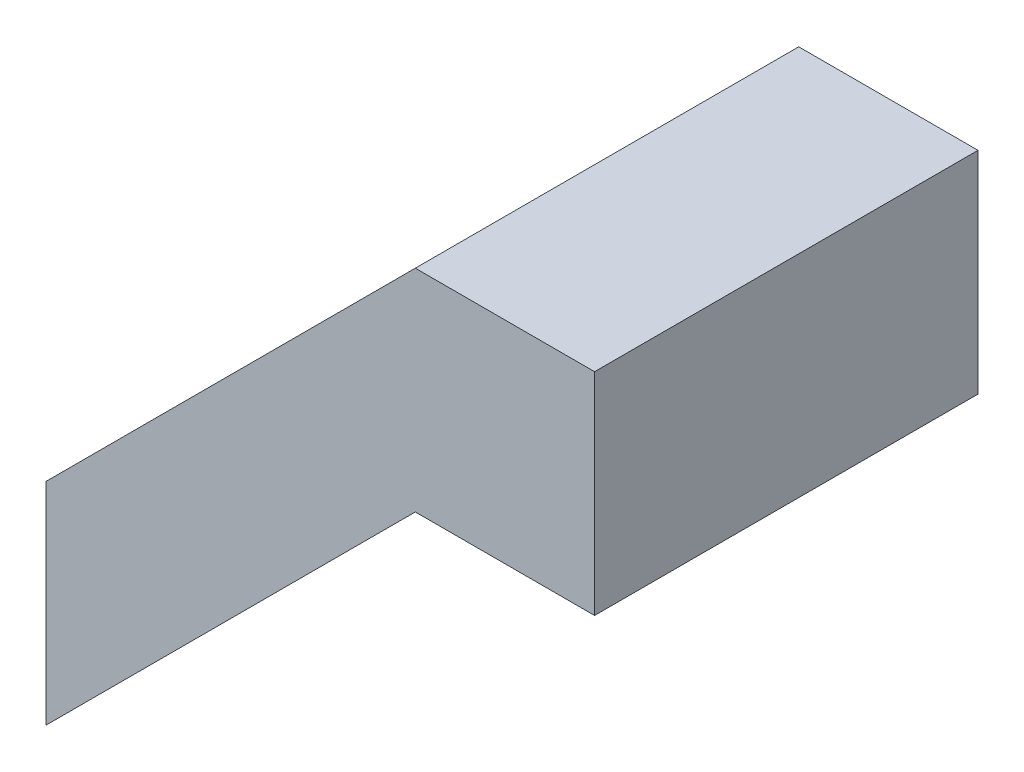
SolidWorks part; units mm, degrees
ref_plane "Alzado" through (0, 0, 0) normal (0, 0, 1) x (1, 0, 0)
ref_plane "Planta" through (0, 0, 0) normal (0, 1, 0) x (1, 0, 0)
ref_plane "Vista lateral" through (0, 0, 0) normal (1, 0, 0) x (0, 0, -1)
sketch "Croquis1" plane through (0, 0, 0) normal (0, 0, 1) x (1, 0, 0)
  line L0 (126.2451, -55.9999) -> (126.2451, -50.9999)
  line L1 (113.2545, -64.7452) -> (113.2545, -59.7452)
  line L2 (121.9998, -55.9999) -> (121.9998, -50.9999) construction
  line L3 (126.2451, -50.9999) -> (121.9998, -50.9999)
  line L4 (121.9998, -50.9999) -> (113.2545, -59.7452)
  line L5 (126.2451, -55.9999) -> (121.9998, -55.9999)
  line L7 (113.2545, -64.7452) -> (115.2545, -62.7452)
  line L8 (115.2545, -62.7452) -> (115.2545, -60.2452)
  line L15 (119.2545, -58.7452) -> (119.2545, -56.2452)
  line L16 (119.2545, -56.2452) -> (115.2545, -60.2452)
  line L17 (121.9998, -55.9999) -> (119.2545, -58.7452)
  dimension "D1" = 50.9999
  dimension "D2" = 56.2452
extrude "Saliente-Extruir1" add sketch "Croquis1" against normal up to vertex (9.08 mm away)
sketch "Croquis4" plane through (0, 0, 0) normal (0, 0, 1) x (1, 0, 0)
  line L3 (115.2545, -60.2452) -> (115.2545, -62.7452)
  line L4 (115.2545, -60.2452) -> (119.2545, -56.2452)
  line L5 (119.2545, -56.2452) -> (119.2545, -58.7452)
  line L6 (119.2545, -58.7452) -> (115.2545, -62.7452)
extrude "Saliente-Extruir4" add sketch "Croquis4" against normal up to vertex (1.5 mm away)
sketch "Croquis5" plane through (0, 0, -9.08) normal (0, 0, -1) x (-1, 0, 0)
  line L2 (-115.2545, -60.2452) -> (-115.2545, -62.7452)
  line L4 (-119.2545, -56.2452) -> (-119.2545, -58.7452)
  line L5 (-119.2545, -58.7452) -> (-115.2545, -62.7452)
  line L6 (-119.2545, -56.2452) -> (-115.2545, -60.2452)
extrude "Saliente-Extruir5" add sketch "Croquis5" against normal up to vertex (4.08 mm away)
